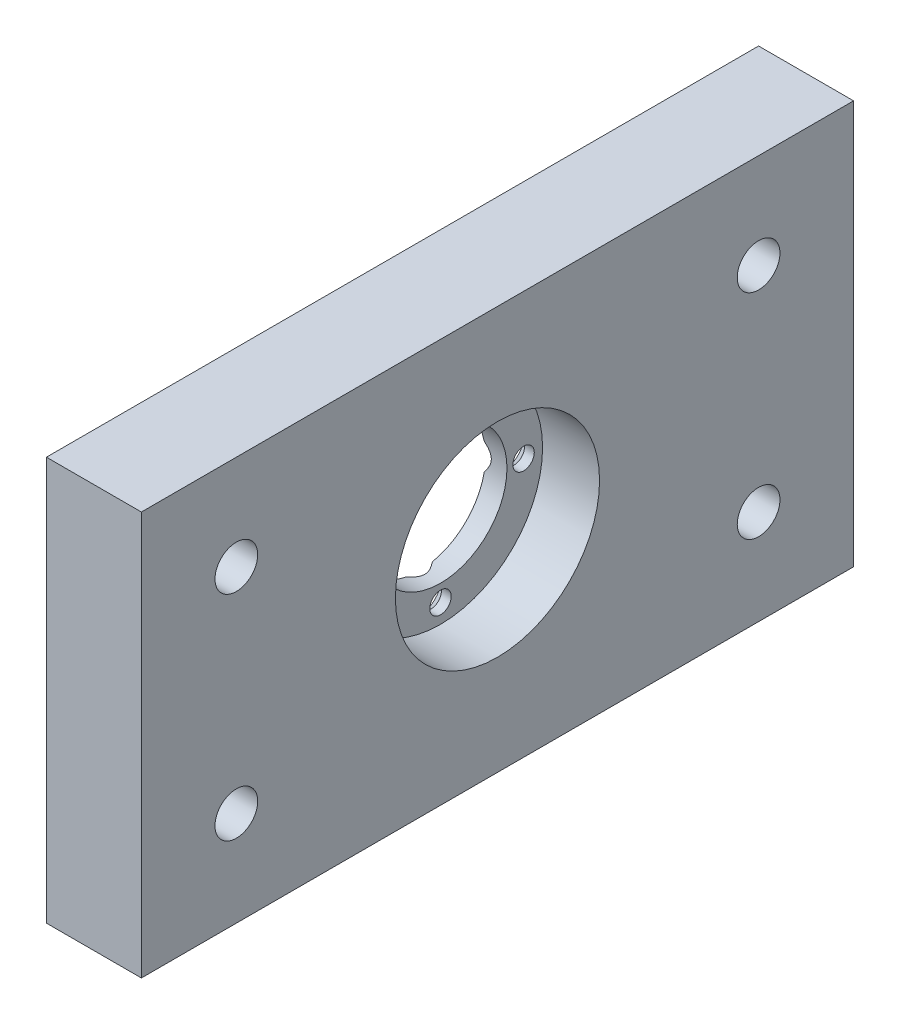
SolidWorks part; units mm, degrees
ref_plane "Front Plane" through (0, 0, 0) normal (0, 0, 1) x (1, 0, 0)
ref_plane "Top Plane" through (0, 0, 0) normal (0, 1, 0) x (1, 0, 0)
ref_plane "Right Plane" through (0, 0, 0) normal (1, 0, 0) x (0, 0, -1)
ref_plane "Plane1" through (152.2448, 0, 0) normal (-1, 0, 0) x (0, 0, 1)
sketch "Sketch1" plane through (152.2448, 0, 0) normal (-1, 0, 0) x (0, 0, 1)
  line L0 (-858.4014, 194.3793) -> (-1008.4014, 109.3793) construction
  line L1 (-1008.4014, 194.3793) -> (-858.4014, 194.3793)
  line L2 (-1008.4014, 194.3793) -> (-1008.4014, 109.3793)
  line L3 (-1008.4014, 109.3793) -> (-858.4014, 109.3793)
  line L4 (-858.4014, 194.3793) -> (-858.4014, 109.3793)
  dimension "D1" = 85
  dimension "D2" = 150
extrude "Boss-Extrude1" add sketch "Sketch1" against normal blind 15.25 and the other way offset from surface (4.75 mm away) 0.5
sketch "Sketch2" plane through (167.4948, 0, 0) normal (1, 0, 0) x (0, 0, -1)
  circle A0 centre (933.4014, 151.8793) radius 21.5
  dimension "D1" = 43
extrude "1mm clearance" cut sketch "Sketch2" against normal blind 12
sketch "M8" plane through (147.4948, 0, 0) normal (-1, 0, 0) x (0, 0, 1)
  line L1 (-878.4014, 196.2738) -> (-878.4014, 162.4603) construction
  line L2 (-933.4014, 194.3793) -> (-933.4014, 109.3793) construction
  line L3 (-858.4014, 194.3793) -> (-1008.4014, 194.3793) construction
  line L4 (-1008.4014, 109.3793) -> (-858.4014, 109.3793) construction
  circle A0 centre (-878.4014, 174.3793) radius 4.5
  circle A1 centre (-878.4014, 129.3793) radius 4.5
  circle A2 centre (-988.4014, 129.3793) radius 4.5
  circle A3 centre (-988.4014, 174.3793) radius 4.5
  dimension "D1" = 9
  dimension "D2" = 9
  dimension "D3" = 20
  dimension "D4" = 20
  dimension "D5" = 110
sketch "M4" plane through (147.4948, 0, 0) normal (-1, 0, 0) x (0, 0, 1)
  circle A0 centre (-933.4014, 169.3793) radius 2.25
  circle A1 centre (-915.9014, 151.8793) radius 2.25
  circle A2 centre (-933.4014, 134.3793) radius 2.25
  circle A3 centre (-950.9014, 151.8793) radius 2.25
  dimension "D1" = 4.5
  dimension "D2" = 4.5
  dimension "D3" = 4.5
  dimension "D4" = 4.5
sketch "Sketch5" plane through (147.4948, 0, 0) normal (-1, 0, 0) x (0, 0, 1)
  circle A0 centre (-933.4014, 151.8793) radius 41
  dimension "D1" = 82
extrude "Cut-Extrude2" cut sketch "Sketch5" against normal blind 3.5
sketch "Sketch6" plane through (150.9948, 0, 0) normal (-1, 0, 0) x (0, 0, 1)
  circle A0 centre (-933.4014, 151.8793) radius 14
  dimension "D1" = 28
extrude "Cut-Extrude3" cut sketch "Sketch6" against normal blind 11.5
hole_wizard "CSK for M8 Flat Head Machine Screw1" positions "Sketch8" profile "Sketch7" countersink size "M8" standard "ANSI Metric" end condition through all
sketch "Sketch8" plane through (147.4948, 0, 0) normal (-1, 0, 0) x (0, 0, 1)
  point P0 (-878.4014, 129.3793)
  point P4 (-878.4014, 174.3793)
  point P7 (-988.4014, 129.3793)
  point P9 (-988.4014, 174.3793)
sketch "Sketch7" plane through (147.4948, 129.3793, -878.4014) normal (0, 1, 0) x (0, 0, 1)
  line L0 (0, 0) -> (0, 20)
  line L1 (0, 20) -> (4.5, 20)
  line L2 (4.5, 20) -> (4.5, 4.15)
  line L3 (4.5, 4.15) -> (8.65, 0)
  line L5 (8.65, 0) -> (0, 0)
  line L6 (-4.5, 4.15) -> (-8.65, 0) construction
  line L11 (0, -6.35) -> (0, 107.95) construction
  dimension "Thru Hole Dia." = 9
  dimension "Thru Hole Depth" = 20
  dimension "Near C'Sink Dia." = 17.3
  dimension "Near C'Sink Angle" = 90
hole_wizard "CSK for M4 Flat Head Machine Screw1" positions "Sketch10" profile "Sketch9" countersink size "M4" standard "ANSI Metric" end condition through all
sketch "Sketch10" plane through (150.9948, 0, 0) normal (-1, 0, 0) x (0, 0, 1)
  point P0 (-933.4014, 134.3793)
  point P3 (-950.9014, 151.8793)
  point P5 (-915.9014, 151.8793)
  point P7 (-933.4014, 169.3793)
sketch "Sketch9" plane through (150.9948, 134.3793, -933.4014) normal (0, 1, 0) x (0, 0, 1)
  line L0 (0, 0) -> (0, 16.5)
  line L1 (0, 16.5) -> (2.25, 16.5)
  line L2 (2.25, 16.5) -> (2.25, 2.45)
  line L3 (2.25, 2.45) -> (4.7, 0)
  line L5 (4.7, 0) -> (0, 0)
  line L6 (-2.25, 2.45) -> (-4.7, 0) construction
  line L11 (0, -6.35) -> (0, 107.95) construction
  dimension "Thru Hole Dia." = 4.5
  dimension "Thru Hole Depth" = 16.5
  dimension "Near C'Sink Dia." = 9.4
  dimension "Near C'Sink Angle" = 90
hole_wizard "M4x0.7 Tapped Hole1" positions "Sketch12" profile "Sketch11" tap size "M4x0.7" standard "ANSI Metric"
sketch "Sketch12" plane through (147.4948, 0, 0) normal (-1, 0, 0) x (0, 0, 1)
  point P0 (-878.4014, 151.8793)
  point P4 (-973.4014, 121.8793)
  point P7 (-973.4014, 181.8793)
cosmetic thread "Hole Thread2" parameters "D1"=10, "D2"=4
cosmetic thread "Hole Thread3" parameters "D1"=10, "D2"=4
cosmetic thread "Hole Thread4" parameters "D1"=10, "D2"=4
sketch "Sketch11" plane through (147.4948, 151.8793, -878.4014) normal (0, 1, 0) x (0, 0, 1)
  line L0 (0, 0) -> (0, 11.0914)
  line L1 (0, 11.0914) -> (1.65, 10.1)
  line L2 (1.65, 10.1) -> (1.65, 0)
  line L5 (1.65, 0) -> (0, 0)
  line L10 (0, 11.0914) -> (-1.65, 10.1) construction
  line L11 (0, -6.35) -> (0, 107.95) construction
  dimension "Tap Drill Dia." = 3.3
  dimension "Tap Drill Depth" = 10.1
  dimension "Drill Angle" = 118
